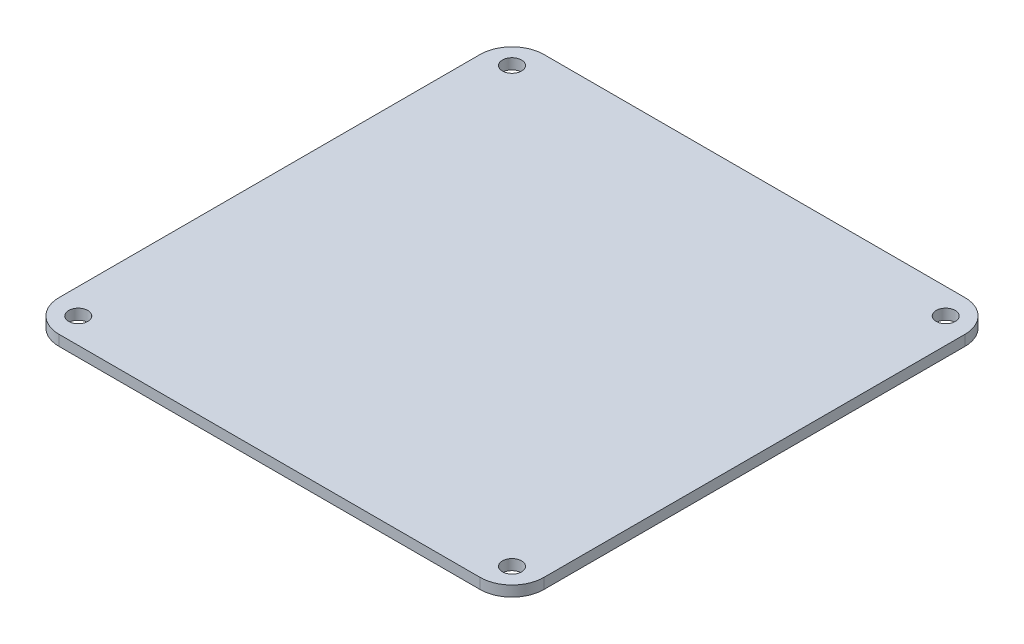
SolidWorks part; units mm, degrees
ref_plane "前视基准面" through (0, 0, 0) normal (0, 0, 1) x (1, 0, 0)
ref_plane "上视基准面" through (0, 0, 0) normal (0, 1, 0) x (1, 0, 0)
ref_plane "右视基准面" through (0, 0, 0) normal (1, 0, 0) x (0, 0, -1)
other "Configuration Table"
sketch "草图1" plane through (0, 0, 0) normal (0, 1, 0) x (1, 0, 0)
  line L0 (0, -19.0184) -> (0, 19.0184) construction
  line L1 (-33, -38) -> (33, -38)
  line L2 (-38, -33) -> (-38, 33)
  line L3 (-33, 38) -> (33, 38)
  line L4 (38, -33) -> (38, 33)
  line L5 (-38, -38) -> (38, 38) construction
  line L6 (-38, 38) -> (38, -38) construction
  line L7 (-34, 34) -> (34, 34)
  line L8 (-34, 34) -> (-34, -34)
  line L9 (-34, -34) -> (34, -34)
  line L10 (34, 34) -> (34, -34)
  line L11 (-34, 34) -> (34, -34) construction
  line L12 (-34, -34) -> (34, 34) construction
  line L13 (-15.8651, 0) -> (15.8651, 0) construction
  arc A0 (38, 33) -> (33, 38) centre (33, 33) ccw
  arc A1 (38, -33) -> (33, -38) centre (33, -33) cw
  arc A2 (-33, -38) -> (-38, -33) centre (-33, -33) cw
  arc A3 (-38, 33) -> (-33, 38) centre (-33, 33) cw
  circle A5 centre (-34, -34) radius 1.5
  circle A6 centre (34, -34) radius 1.5
  circle A7 centre (-34, 34) radius 1.5
  circle A8 centre (34, 34) radius 1.5
  point P0 (0, 0)
  point P18 (0, 0)
  point P27 (0, 0)
  point P30 (0, 0)
  dimension "D3" = 5
  dimension "D1" = 76
  dimension "D2" = 76
extrude "凸台-拉伸1" add sketch "草图1" along normal blind 1.65 contours A3 L2 A2 L1 A1 L4 A0 L3 A8 L10 A6 L9 A5 L8 A7 L7 | A8 L7 A7 L8 A5 L9 A6 L10
